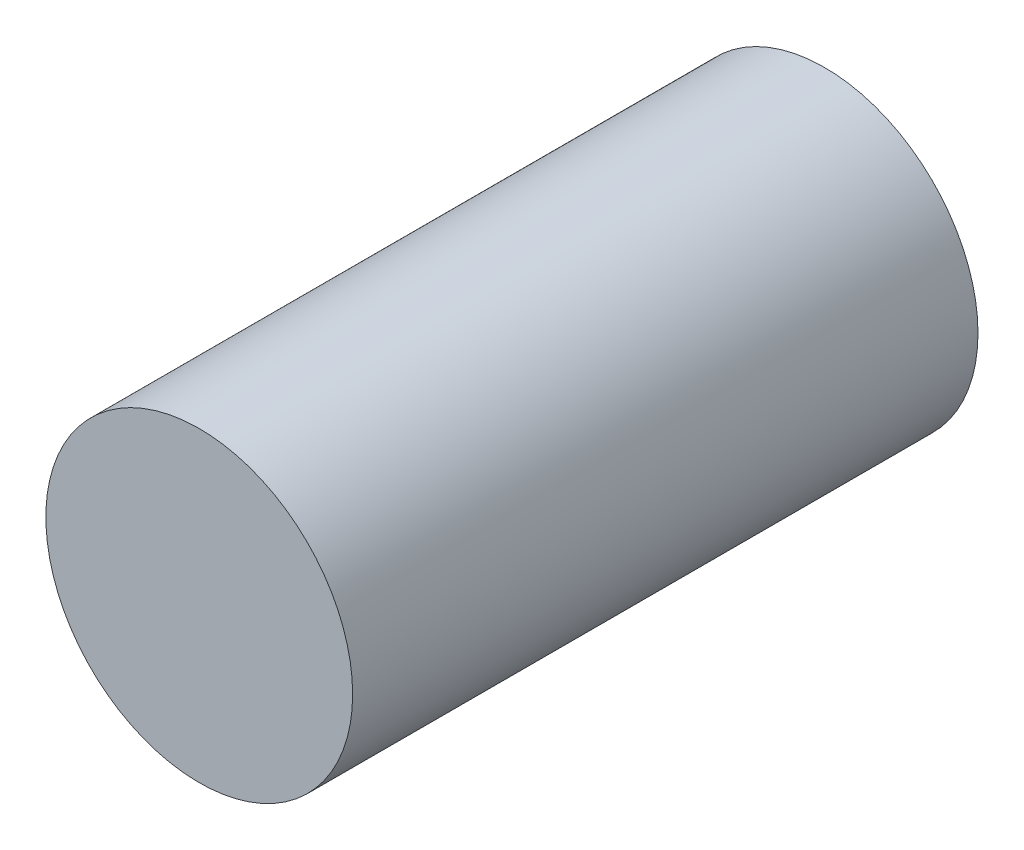
SolidWorks part; units mm, degrees
ref_plane "Plan de face" through (0, 0, 0) normal (0, 0, 1) x (1, 0, 0)
ref_plane "Plan de dessus" through (0, 0, 0) normal (0, 1, 0) x (1, 0, 0)
ref_plane "Plan de droite" through (0, 0, 0) normal (1, 0, 0) x (0, 0, -1)
sketch "Esquisse1" plane through (0, 0, 0) normal (0, 0, 1) x (1, 0, 0)
  circle A0 centre (0, 0) radius 6.5
  dimension "D1" = 13
extrude "Extrusion1" add sketch "Esquisse1" along normal blind 26.5
